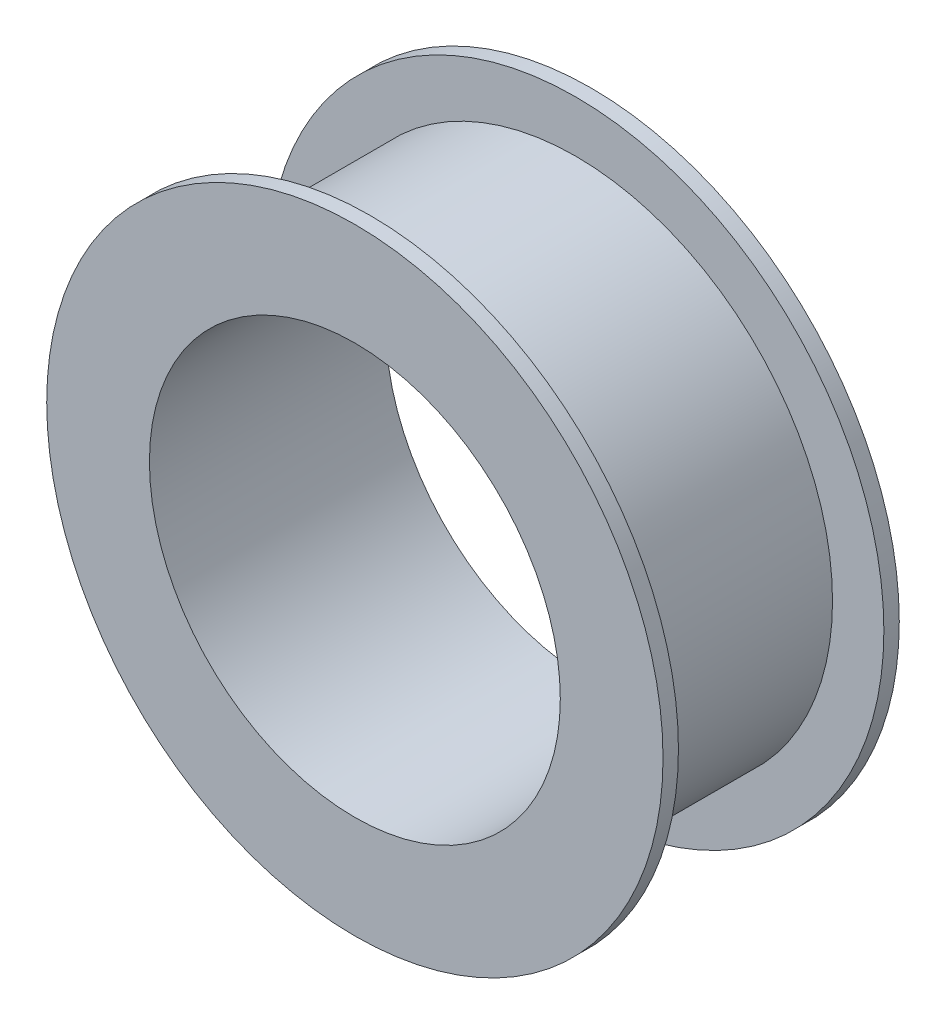
SolidWorks part; units mm, degrees
ref_plane "Alzado" through (0, 0, 0) normal (0, 0, 1) x (1, 0, 0)
ref_plane "Planta" through (0, 0, 0) normal (0, 1, 0) x (1, 0, 0)
ref_plane "Vista lateral" through (0, 0, 0) normal (1, 0, 0) x (0, 0, -1)
sketch "Croquis1" plane through (0, 0, 0) normal (0, 0, 1) x (1, 0, 0)
  circle A0 centre (0, 0) radius 40
  circle A1 centre (0, 0) radius 50
  dimension "D1" = 80
  dimension "D2" = 10
extrude "Saliente-Extruir2" add sketch "Croquis1" along normal blind 40
sketch "Croquis2" plane through (0, 0, 40) normal (0, 0, 1) x (1, 0, 0)
  circle A0 centre (0, 0) radius 60
  circle A1 centre (0, 0) radius 40
  dimension "D1" = 120
extrude "Saliente-Extruir3" add sketch "Croquis2" along normal blind 3
sketch "Croquis3" plane through (0, 0, 0) normal (0, 0, -1) x (-1, 0, 0)
  circle A0 centre (0, 0) radius 60
  circle A1 centre (0, 0) radius 40
  dimension "D1" = 120
extrude "Saliente-Extruir4" add sketch "Croquis3" along normal blind 3
